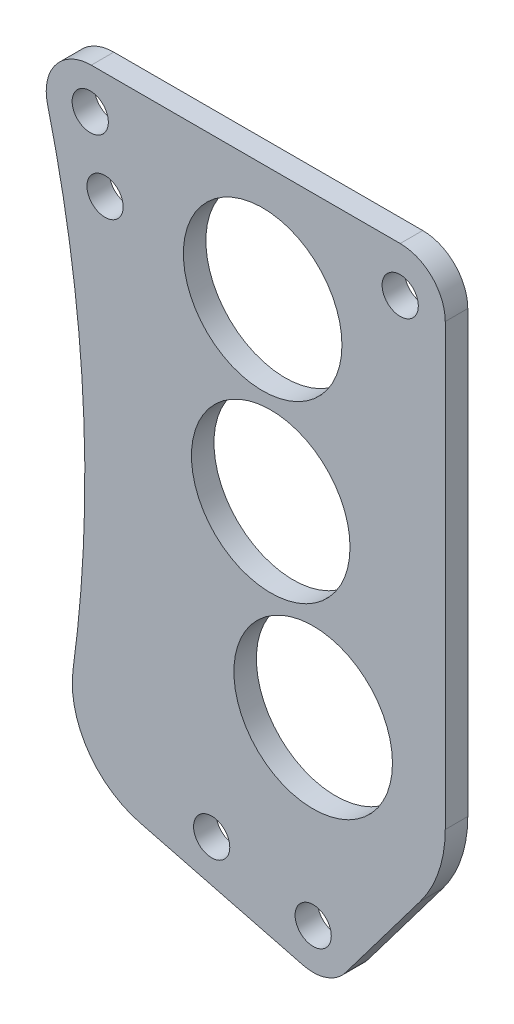
SolidWorks part; units mm, degrees
material "Polypropylene"
ref_plane "Front Plane" through (0, 0, 0) normal (0, 0, 1) x (1, 0, 0)
ref_plane "Top Plane" through (0, 0, 0) normal (0, 1, 0) x (1, 0, 0)
ref_plane "Right Plane" through (0, 0, 0) normal (1, 0, 0) x (0, 0, -1)
sketch "Sketch2" plane through (0, 0, 0) normal (0, 0, 1) x (1, 0, 0)
  line L0 (-139.7, 0) -> (139.7, 0) construction
  line L1 (-139.7, 162.1582) -> (139.7, 162.1582) construction
  line L2 (-139.7, 0) -> (-139.7, 162.1582) construction
  line L3 (89.6578, 156.3951) -> (-88.9, 111.3582) construction
  line L4 (-88.9, 111.3582) -> (87.5277, 58.5898) construction
  line L6 (85.725, 52.9003) -> (82.55, 52.9003) construction
  line L7 (139.7, 162.1582) -> (139.7, 0) construction
  line L8 (-109.7, 30) -> (-102.2692, 59.0652) construction
  line L9 (-102.2692, 59.0652) -> (-101.4828, 62.1412) construction
  line L10 (-101.4828, 62.1412) -> (-88.9, 111.3582) construction
  line L11 (-88.9, 111.3582) -> (85.725, 52.9003) construction
  line L12 (82.55, 52.9003) -> (82.55, 64.2654) construction
  line L13 (-88.9, 111.3582) -> (91.7477, 147.1022) construction
  line L14 (82.55, 52.9003) -> (85.725, 0) construction
  line L15 (85.725, 52.9003) -> (92.4089, 52.9003) construction
  line L16 (-131.5562, 154.0144) -> (-88.9, 111.3582) construction
  line L17 (-88.9, 111.3582) -> (88.9, 111.3582) construction
  line L18 (-88.9, 111.3582) -> (88.1045, 162.1582) construction
  line L22 (82.8416, 162.1582) -> (82.8416, 157.3763) construction
  line L23 (82.8416, 157.3763) -> (-88.9, 111.3582) construction
  line L24 (122.2, 93.8006) -> (115.1001, 121.5451) construction
  line L25 (-88.9, 111.3582) -> (-131.5562, 68.702) construction
  line L26 (120.5994, 121.5451) -> (117.8497, 126.3076) construction
  line L27 (117.8497, 126.3076) -> (112.3505, 126.3076) construction
  line L28 (112.3505, 126.3076) -> (109.6008, 121.5451) construction
  line L29 (109.6008, 121.5451) -> (112.3505, 116.7826) construction
  line L30 (112.3505, 116.7826) -> (117.8497, 116.7826) construction
  line L31 (117.8497, 116.7826) -> (120.5994, 121.5451) construction
  line L40 (-139.7, 154.0144) -> (-139.7, 30) construction
  line L41 (-131.5562, 161.3468) -> (-137.9062, 157.6806) construction
  line L42 (-137.9062, 157.6806) -> (-137.9062, 150.3483) construction
  line L43 (-137.9062, 150.3483) -> (-131.5562, 146.6821) construction
  line L44 (-131.5562, 146.6821) -> (-125.2062, 150.3483) construction
  line L45 (-125.2062, 150.3483) -> (-125.2062, 157.6806) construction
  line L46 (-125.2062, 157.6806) -> (-131.5562, 161.3468) construction
  line L47 (-131.5562, 61.3697) -> (-125.2062, 65.0358) construction
  line L48 (-125.2062, 65.0358) -> (-125.2062, 72.3682) construction
  line L49 (-125.2062, 72.3682) -> (-131.5562, 76.0344) construction
  line L50 (-131.5562, 76.0344) -> (-137.9062, 72.3682) construction
  line L51 (-137.9062, 72.3682) -> (-137.9062, 65.0358) construction
  line L52 (-137.9062, 65.0358) -> (-131.5562, 61.3697) construction
  line L53 (-79.9907, 25.8335) -> (-68.3996, 108.4832) construction
  line L54 (-77.6298, 128.7224) -> (-127.1225, 160.8455) construction
  line L56 (89.8048, 162.1582) -> (133.35, 162.1582)
  line L57 (139.7, 155.8082) -> (139.7, 93.8006)
  line L59 (137.8401, 160.2984) -> (129.3001, 151.7583) construction
  line L60 (122.2, 93.8006) -> (110.579, 80.7162) construction
  line L61 (110.579, 80.7162) -> (106.7754, 76.4337) construction
  line L62 (98.6364, 77.8864) -> (101.1368, 77.4401) construction
  line L63 (98.6364, 77.8864) -> (-88.9, 111.3582) construction
  line L64 (106.7754, 76.4337) -> (108.5394, 70.9844) construction
  line L69 (101.1368, 77.4401) -> (106.7754, 76.4337) construction
  line L70 (121.0823, 72.7684) -> (121.0823, 98.1684) construction
  line L71 (125.6552, 69.3194) -> (136.1716, 83.2629)
  line L72 (96.6729, 73.1093) -> (119.6608, 67.2199)
  line L73 (106.7754, 76.4337) -> (121.0823, 72.7684) construction
  circle A0 centre (-88.9, 111.3582) radius 50.8 construction
  circle A1 centre (-88.9, 111.3582) radius 14.351 construction
  arc A15 (81.4439, 60.4094) -> (81.4884, 162.1582) centre (-88.9, 111.3582) ccw construction
  arc A16 (92.4089, 52.9003) -> (94.7018, 162.1582) centre (-88.9, 111.3582) ccw construction
  arc A17 (89.6578, 156.3951) -> (87.5277, 58.5898) centre (-88.9, 111.3582) cw construction
  arc A18 (90.2045, 57.7892) -> (92.367, 157.0784) centre (-88.9, 111.3582) ccw construction
  arc A19 (84.8508, 59.3905) -> (86.9487, 155.7118) centre (-88.9, 111.3582) ccw construction
  arc A20 (84.8508, 59.3905) -> (90.2045, 57.7892) centre (87.5277, 58.5898) ccw construction
  arc A21 (92.367, 157.0784) -> (86.9487, 155.7118) centre (89.6578, 156.3951) ccw construction
  arc A23 (89.6578, 156.3951) -> (88.1045, 162.1582) centre (-88.9, 111.3582) ccw construction
  circle A24 centre (113.9624, 145.6482) radius 15.24 construction
  circle A25 centre (122.2, 93.8006) radius 17.5 construction
  circle A26 centre (122.2, 93.8006) radius 4.826 construction
  circle A27 centre (115.1001, 121.5451) radius 23.8125 construction
  circle A28 centre (113.9624, 145.6482) radius 16.51 construction
  circle A29 centre (-109.7, 30) radius 30 construction
  circle A30 centre (-109.7, 30) radius 25.4 construction
  circle A31 centre (-109.7, 55.4) radius 2.5527 construction
  circle A32 centre (-97, 51.997) radius 2.5527 construction
  circle A33 centre (-87.703, 42.7) radius 2.5527 construction
  circle A34 centre (-84.3, 30) radius 2.5527 construction
  circle A35 centre (-87.703, 17.3) radius 2.5527 construction
  circle A36 centre (-97, 8.003) radius 2.5527 construction
  circle A37 centre (-109.7, 4.6) radius 2.5527 construction
  circle A38 centre (-122.4, 8.003) radius 2.5527 construction
  circle A39 centre (-131.697, 17.3) radius 2.5527 construction
  circle A40 centre (-135.1, 30) radius 2.5527 construction
  circle A41 centre (-131.697, 42.7) radius 2.5527 construction
  circle A42 centre (-122.4, 51.997) radius 2.5527 construction
  arc A43 (87.5277, 58.5898) -> (85.725, 52.9003) centre (-88.9, 111.3582) cw construction
  circle A44 centre (-109.7, 30) radius 14.351 construction
  circle A48 centre (115.1001, 121.5451) radius 24.5999 construction
  circle A54 centre (115.1001, 121.5451) radius 4.7625 construction
  circle A55 centre (115.1001, 121.5451) radius 8.89 construction
  circle A56 centre (115.1001, 121.5451) radius 10.16 construction
  circle A59 centre (113.9624, 145.6482) radius 15.24 construction
  circle A60 centre (113.9624, 145.6482) radius 16.51 construction
  circle A61 centre (89.6578, 156.3951) radius 2.5527
  circle A62 centre (91.7477, 147.1022) radius 2.5527
  circle A63 centre (-131.5562, 68.702) radius 3.175 construction
  circle A64 centre (-131.5562, 154.0144) radius 3.175 construction
  circle A65 centre (-131.5562, 154.0144) radius 6.35 construction
  circle A66 centre (-131.5562, 68.702) radius 6.35 construction
  arc A67 (-139.7, 30) -> (-79.9907, 25.8335) centre (-109.7, 30) ccw construction
  arc A69 (-127.1225, 160.8455) -> (-139.7, 154.0144) centre (-131.5562, 154.0144) ccw construction
  arc A70 (-68.3996, 108.4832) -> (-77.6298, 128.7224) centre (-88.9, 111.3582) ccw construction
  arc A71 (139.7, 93.8006) -> (136.1716, 83.2629) centre (122.2, 93.8006) cw
  arc A72 (83.6426, 154.2755) -> (87.2431, 87.1417) centre (-88.9, 111.3582) cw
  arc A73 (87.2431, 87.1417) -> (96.6729, 73.1093) centre (99.8248, 85.4119) ccw
  arc A74 (133.35, 162.1582) -> (139.7, 155.8082) centre (133.35, 155.8082) cw
  circle A76 centre (106.7754, 76.4337) radius 2.5527
  circle A82 centre (115.1001, 121.5451) radius 11.176
  arc A83 (83.6426, 154.2755) -> (89.8048, 162.1582) centre (89.8048, 155.8082) cw
  circle A84 centre (113.9624, 145.6482) radius 11.176
  circle A87 centre (133.35, 155.8082) radius 2.5527
  circle A89 centre (121.0823, 72.7684) radius 2.5527
  arc A90 (119.6608, 67.2199) -> (125.6552, 69.3194) centre (121.0823, 72.7684) ccw
  circle A91 centre (121.0823, 98.1684) radius 15.24 construction
  circle A92 centre (121.0823, 98.1684) radius 16.51 construction
  circle A93 centre (121.0823, 98.1684) radius 11.176
  point P6 (-88.9, 60.5582)
  point P10 (-109.7, 0)
  point P11 (86.727, 55.913)
  point P30 (-88.9, 111.3582)
  point P32 (0, 0)
  point P36 (0, 162.1582)
  point P37 (-88.9, 162.1582)
  point P42 (95.2063, 107.3484)
  point P66 (-109.7, 30)
  point P68 (-139.7, 30)
  point P82 (88.954, 159.099)
  point P85 (-79.7, 30)
  point P92 (88.1045, 162.1582)
  point P105 (122.2, 93.8006)
  point P138 (132.0087, 101.5491)
  point P142 (107.5616, 74.0051)
  point P171 (130.9475, 102.7298)
  dimension "D1" = 101.6
  dimension "D2" = 28.702
  dimension "D3" = 60
  dimension "D4" = 50.8
  dimension "D9" = 127
  dimension "D10" = 12.7
  dimension "D11" = 6.35
  dimension "D12" = 2.794
  dimension "D16" = 35
  dimension "D17" = 9.652
  dimension "D18" = 47.625
  dimension "D19" = 30.48
  dimension "D20" = 30.48
  dimension "D5" = 5.1054
  dimension "D13" = 85.725
  dimension "D25" = 28.702
  dimension "D21" = 82.55
  dimension "D22" = 186.944
  dimension "D30" = 49.1998
  dimension "D31" = 60.325
  dimension "D32" = 27.844
  dimension "D33" = 12.7
  dimension "D34" = 1.27
  dimension "D35" = 25.4
  dimension "D37" = 9.525
  dimension "D38" = 17.78
  dimension "D39" = 20.32
  dimension "D40" = 6.35
  dimension "D41" = 6.35
  dimension "D42" = 1.27
  dimension "D43" = 1.27
  dimension "D44" = 12.7
  dimension "D45" = 3.175
  dimension "D28" = 5.1054
  dimension "D29" = 6.35
  dimension "D47" = 22.352
  dimension "D48" = 6.35
  dimension "D49" = 22.352
  dimension "D53" = 5.1054
  dimension "D51" = 5.1054
  dimension "D55" = 2.54
  dimension "D56" = 1.5875
  dimension "D36" = 3.175
  dimension "D6" = 12
  dimension "D7" = 15
  dimension "D8" = 279.4
  dimension "D14" = 3.175
  dimension "D15" = 279.4
  dimension "D23" = 3.175
  dimension "D24" = 3.175
  dimension "D26" = 3.175
  dimension "D27" = 9.525
  dimension "D50" = 12.0774
extrude "Boss-Extrude1" add sketch "Sketch2" along normal blind 3.175
